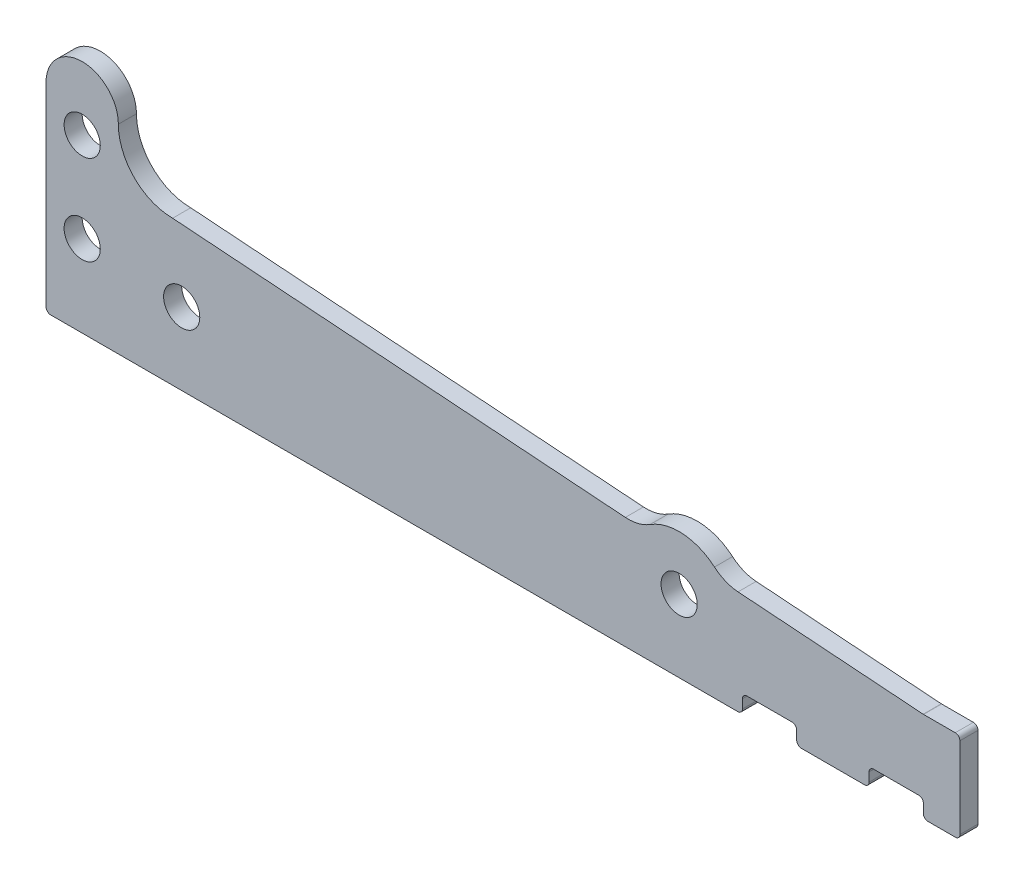
SolidWorks part; units mm, degrees
ref_plane "Front Plane" through (0, 0, 0) normal (0, 0, 1) x (1, 0, 0)
ref_plane "Top Plane" through (0, 0, 0) normal (0, 1, 0) x (1, 0, 0)
ref_plane "Right Plane" through (0, 0, 0) normal (1, 0, 0) x (0, 0, -1)
sketch "Sketch1" plane through (0, 0, 0) normal (0, 0, 1) x (1, 0, 0)
  line L0 (3.175, 19.05) -> (3.175, 0) construction
  line L1 (0, 0) -> (6.35, 0) construction
  line L2 (0, 0) -> (0, 19.05)
  line L3 (0, 19.05) -> (6.35, 19.05)
  line L4 (6.35, 0) -> (6.35, 19.05) construction
  line L5 (3.175, 13.462) -> (3.175, 5.588) construction
  line L6 (6.35, 0) -> (76.9897, 0) construction
  line L9 (0, 0) -> (0, -1.5875)
  line L11 (76.9897, -1.5875) -> (76.9897, 0)
  line L12 (0, 19.05) -> (-1.5875, 19.05) construction
  line L13 (-1.5875, 19.05) -> (-1.5875, -1.5875) construction
  line L14 (-1.5875, -1.5875) -> (0, -1.5875) construction
  line L15 (76.9897, 11.1125) -> (6.35, 11.1125) construction
  line L16 (76.9897, 0) -> (76.9897, 11.1125) construction
  line L17 (11.1125, 11.1125) -> (76.9897, 6.35)
  line L18 (76.9897, 6.35) -> (76.9897, 0)
  line L19 (76.9897, -1.5875) -> (80.197, -1.5875)
  line L20 (76.9897, 6.35) -> (80.197, 6.35)
  line L21 (80.197, 6.35) -> (80.197, -1.5875)
  line L22 (76.9897, 0) -> (72.2272, 0)
  line L23 (72.2272, 0) -> (72.2272, -1.5875)
  line L24 (72.2272, -1.5875) -> (65.8772, -1.5875)
  line L25 (65.8772, -1.5875) -> (65.8772, 0)
  line L26 (65.8772, 0) -> (61.1147, 0)
  line L27 (61.1147, 0) -> (61.1147, -1.5875)
  line L28 (0, -1.5875) -> (61.1147, -1.5875)
  line L29 (61.1147, -1.5875) -> (76.9897, -1.5875)
  line L30 (11.9062, -1.5875) -> (11.9062, 4.7625) construction
  line L31 (55.5585, -1.5875) -> (55.5585, 4.7625) construction
  circle A0 centre (3.175, 13.462) radius 1.5875
  circle A1 centre (3.175, 5.588) radius 1.5875
  circle A2 centre (3.175, 15.875) radius 3.175
  circle A3 centre (3.175, 3.175) radius 3.175
  circle A4 centre (11.1125, 15.875) radius 4.7625
  circle A5 centre (11.9062, 4.7625) radius 1.5875
  circle A6 centre (55.5585, 4.7625) radius 1.5875
  circle A7 centre (55.5585, 4.7625) radius 4.7625
  point P11 (3.175, 9.525)
  point P12 (3.175, 9.525)
  point P30 (6.35, 15.875)
  dimension "D1" = 19.05
  dimension "D2" = 3.175
  dimension "D8" = 11.1125
  dimension "D9" = 6.35
  dimension "D10" = 3.2072
  dimension "D13" = 6.35
  dimension "D14" = 5.5562
  dimension "D3" = 6.35
  dimension "D4" = 7.874
  dimension "D5" = 1.5875
  dimension "D6" = 78.5772
  dimension "D7" = 1.5875
  dimension "D11" = 15.875
  dimension "D12" = 6.35
  dimension "D15" = 5.5562
extrude "Boss-Extrude1" add sketch "Sketch1" along normal blind 1.5875
fillet "Fillet1" radius 0.4064 12 edges at (76.9897, 6.35, 0.7937) (80.197, 6.35, 0.7937) (80.197, -1.5875, 0.7937) (72.2272, 0, 0.7937) (61.1147, 0, 0.7937) (76.9897, 0, 0.7937) (76.9897, -1.5875, 0.7937) (65.8772, 0, 0.7937) (72.2272, -1.5875, 0.7937) (65.8772, -1.5875, 0.7937) (61.1147, -1.5875, 0.7937) (0, -1.5875, 0.7937)
fillet "Fillet2" radius 3.5719 2 edges at (52.2028, 8.1419, 0.7937) (59.3654, 7.6241, 0.7937)
